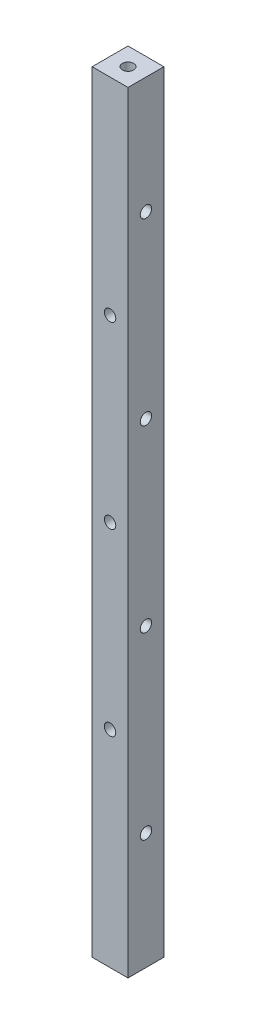
SolidWorks part; units mm, degrees
ref_plane "Front Plane" through (0, 0, 0) normal (0, 0, 1) x (1, 0, 0)
ref_plane "Top Plane" through (0, 0, 0) normal (0, 1, 0) x (1, 0, 0)
ref_plane "Right Plane" through (0, 0, 0) normal (1, 0, 0) x (0, 0, -1)
sketch "Sketch1" plane through (0, 0, 0) normal (0, 1, 0) x (1, 0, 0)
  line L1 (-6.35, -6.35) -> (6.35, -6.35)
  line L2 (-6.35, -6.35) -> (-6.35, 6.35)
  line L3 (-6.35, 6.35) -> (6.35, 6.35)
  line L4 (6.35, -6.35) -> (6.35, 6.35)
  line L5 (-6.35, -6.35) -> (6.35, 6.35) construction
  line L6 (-6.35, 6.35) -> (6.35, -6.35) construction
  point P0 (0, 0)
  dimension "D1" = 12.7
extrude "Boss-Extrude1" add sketch "Sketch1" along normal mid plane 273.05
sketch "Sketch2" [suppressed] plane through (0, 0, 6.35) normal (0, 0, 1) x (1, 0, 0)
  line L0 (0, -6.985) -> (0, 6.985) construction
  line L1 (-6.35, 247.65) -> (6.35, 247.65) construction
  point P0 (0, 241.3)
  point P7 (0, 144.78)
  point P8 (0, 48.26)
  point P9 (0, -48.26)
  point P10 (0, -144.78)
  point P11 (0, -241.3)
  dimension "D1" = 6.35
  dimension "D2" = 6
hole_wizard "#10 Clearance Hole1" [suppressed] positions "Sketch5" profile "Sketch7" hole size "#10" standard "ANSI Inch"
sketch "Sketch5" plane through (0, 0, 6.35) normal (0, 0, 1) x (1, 0, 0)
  point P0 (0, 241.3)
  point P3 (0, -241.3)
sketch "Sketch7" plane through (0, 241.3, 6.35) normal (1, 0, 0) x (0, -1, 0)
  line L0 (0, 0) -> (0, 12.7)
  line L1 (0, 12.7) -> (2.5527, 12.7)
  line L2 (2.5527, 12.7) -> (2.5527, 0)
  line L5 (2.5527, 0) -> (0, 0)
  line L11 (0, -6.35) -> (0, 107.95) construction
  dimension "Thru Hole Dia." = 5.1054
  dimension "Thru Hole Depth" = 12.7
hole_wizard "#10-32 Tapped Hole2" [suppressed] positions "Sketch8" profile "Sketch10" tap size "#10-32" standard "ANSI Inch"
sketch "Sketch8" plane through (0, 0, 6.35) normal (0, 0, 1) x (1, 0, 0)
  point P0 (0, 144.78)
  point P6 (0, -144.78)
  point P9 (0, -48.26)
  point P12 (0, 48.26)
sketch "Sketch10" plane through (0, 144.78, 6.35) normal (1, 0, 0) x (0, -1, 0)
  line L0 (0, 0) -> (0, 12.7)
  line L1 (0, 12.7) -> (2.0193, 12.7)
  line L2 (2.0193, 12.7) -> (2.0193, 0)
  line L5 (2.0193, 0) -> (0, 0)
  line L11 (0, -6.35) -> (0, 107.95) construction
  dimension "Thru Tap Drill Dia." = 4.0386
  dimension "Thru Tap Drill Depth" = 12.7
cosmetic thread "Hole Thread7" [suppressed] parameters "D2"=4.826
cosmetic thread "Hole Thread8" [suppressed] parameters "D2"=4.826
cosmetic thread "Hole Thread9" [suppressed] parameters "D2"=4.826
cosmetic thread "Hole Thread10" [suppressed] parameters "D2"=4.826
sketch "Sketch11" plane through (0, -136.525, 0) normal (0, -1, 0) x (1, 0, 0)
  point P0 (0, 0)
hole_wizard "#10-32 Tapped Hole3" positions "Sketch12" profile "Sketch14" tap size "#10-32" standard "ANSI Inch"
sketch "Sketch12" plane through (0, -136.525, 0) normal (0, -1, 0) x (-1, 0, 0)
  point P0 (0, 0)
sketch "Sketch14" plane through (0, -136.525, 0) normal (1, 0, 0) x (0, 0, -1)
  line L0 (0, 0) -> (0, 13.1513)
  line L1 (0, 13.1513) -> (2.0193, 11.938)
  line L2 (2.0193, 11.938) -> (2.0193, 0)
  line L5 (2.0193, 0) -> (0, 0)
  line L10 (0, 13.1513) -> (-2.0193, 11.938) construction
  line L11 (0, -6.35) -> (0, 107.95) construction
  dimension "Tap Drill Dia." = 4.0386
  dimension "Tap Drill Depth" = 11.938
  dimension "Drill Angle" = 118
cosmetic thread "Hole Thread11" parameters "D1"=9.652, "D2"=4.826
mirror "Mirror1" about plane through (0, 0, 0) normal (0, 1, 0) of "#10-32 Tapped Hole3"
cosmetic thread "Hole Thread12" parameters "D1"=9.652, "D2"=4.826
sketch "Sketch15" plane through (0, 0, -6.35) normal (0, 0, -1) x (-1, 0, 0)
  line L0 (0, 6.985) -> (0, -6.985) construction
  point P0 (0, 0)
  point P1 (0, 63.5)
  point P3 (0, -63.5)
  dimension "D1" = 63.5
  dimension "D2" = 63.5
hole_wizard "#10-32 Tapped Hole4" positions "Sketch16" profile "Sketch17" tap size "#10-32" standard "ANSI Inch" end condition up to next
sketch "Sketch16" plane through (0, 0, -6.35) normal (0, 0, -1) x (-1, 0, 0)
  point P0 (0, 63.5)
  point P3 (0, 0)
  point P6 (0, -63.5)
cosmetic thread "Hole Thread13" parameters "D2"=4.826
cosmetic thread "Hole Thread14" parameters "D2"=4.826
cosmetic thread "Hole Thread15" parameters "D2"=4.826
sketch "Sketch17" plane through (0, 63.5, -6.35) normal (1, 0, 0) x (0, 1, 0)
  line L0 (0, 0) -> (0, 12.7)
  line L1 (0, 12.7) -> (2.0193, 12.7)
  line L2 (2.0193, 12.7) -> (2.0193, 0)
  line L5 (2.0193, 0) -> (0, 0)
  line L11 (0, -6.35) -> (0, 107.95) construction
  dimension "Thru Tap Drill Dia." = 4.0386
  dimension "Thru Tap Drill Depth" = 12.7
sketch "Sketch18" plane through (-6.35, 0, 0) normal (-1, 0, 0) x (0, 0, 1)
  line L0 (0, -6.985) -> (0, 6.985) construction
  line L1 (6.985, 0) -> (-6.985, 0) construction
  point P1 (0, 31.75)
  point P2 (0, -31.75)
  point P5 (0, 95.25)
  point P6 (0, -95.25)
  dimension "D1" = 31.75
  dimension "D2" = 31.75
  dimension "D3" = 63.5
  dimension "D4" = 63.5
hole_wizard "#10-32 Tapped Hole5" positions "Sketch19" profile "Sketch20" tap size "#10-32" standard "ANSI Inch" end condition up to next
sketch "Sketch19" plane through (-6.35, 0, 0) normal (-1, 0, 0) x (0, 0, 1)
  point P0 (0, 95.25)
  point P3 (0, 31.75)
  point P6 (0, -31.75)
  point P9 (0, -95.25)
sketch "Sketch20" plane through (-6.35, 95.25, 0) normal (0, 1, 0) x (0, 0, 1)
  line L0 (0, 0) -> (0, 12.7)
  line L1 (0, 12.7) -> (2.0193, 12.7)
  line L2 (2.0193, 12.7) -> (2.0193, 0)
  line L5 (2.0193, 0) -> (0, 0)
  line L11 (0, -6.35) -> (0, 107.95) construction
  dimension "Thru Tap Drill Dia." = 4.0386
  dimension "Thru Tap Drill Depth" = 12.7
cosmetic thread "Hole Thread16" parameters "D2"=4.826
cosmetic thread "Hole Thread17" parameters "D2"=4.826
cosmetic thread "Hole Thread18" parameters "D2"=4.826
cosmetic thread "Hole Thread19" parameters "D2"=4.826
sketch "Sketch21" [suppressed] plane through (-6.35, 0, 0) normal (-1, 0, 0) x (0, 0, 1)
  line L0 (0, -6.985) -> (0, 6.985) construction
  point P0 (0, 0)
  point P1 (0, 96.52)
  point P3 (0, 193.04)
  point P6 (0, -96.52)
  point P7 (0, -193.04)
  dimension "D1" = 96.52
  dimension "D2" = 96.52
  dimension "D3" = 96.52
  dimension "D4" = 96.52
hole_wizard "#10-32 Tapped Hole6" [suppressed] positions "Sketch22" profile "Sketch23" tap size "#10-32" standard "ANSI Inch"
sketch "Sketch22" plane through (-6.35, 0, 0) normal (-1, 0, 0) x (0, 0, 1)
  point P0 (0, 193.04)
  point P3 (0, 96.52)
  point P6 (0, 0)
  point P9 (0, -96.52)
  point P12 (0, -193.04)
sketch "Sketch23" plane through (-6.35, 193.04, 0) normal (0, 1, 0) x (0, 0, 1)
  line L0 (0, 0) -> (0, 12.7)
  line L1 (0, 12.7) -> (2.0193, 12.7)
  line L2 (2.0193, 12.7) -> (2.0193, 0)
  line L5 (2.0193, 0) -> (0, 0)
  line L11 (0, -6.35) -> (0, 107.95) construction
  dimension "Thru Tap Drill Dia." = 4.0386
  dimension "Thru Tap Drill Depth" = 12.7
cosmetic thread "Hole Thread20" [suppressed] parameters "D2"=4.826
cosmetic thread "Hole Thread21" [suppressed] parameters "D2"=4.826
cosmetic thread "Hole Thread22" [suppressed] parameters "D2"=4.826
cosmetic thread "Hole Thread23" [suppressed] parameters "D2"=4.826
cosmetic thread "Hole Thread24" [suppressed] parameters "D2"=4.826
sketch "Sketch24" [suppressed] plane through (6.35, 0, 0) normal (1, 0, 0) x (0, 0, -1)
  point P0 (0, -25.4)
  point P1 (0, -71.12)
hole_wizard "#10-32 Tapped Hole7" [suppressed] positions "Sketch25" profile "Sketch27" tap size "#10-32" standard "ANSI Inch"
sketch "Sketch25" plane through (6.35, 0, 0) normal (1, 0, 0) x (0, 0, -1)
  point P0 (0, -25.4)
  point P4 (0, -71.12)
sketch "Sketch27" plane through (6.35, -25.4, 0) normal (0, 1, 0) x (0, 0, -1)
  line L0 (0, 0) -> (0, 12.7)
  line L1 (0, 12.7) -> (2.0193, 12.7)
  line L2 (2.0193, 12.7) -> (2.0193, 0)
  line L5 (2.0193, 0) -> (0, 0)
  line L11 (0, -6.35) -> (0, 107.95) construction
  dimension "Thru Tap Drill Dia." = 4.0386
  dimension "Thru Tap Drill Depth" = 12.7
cosmetic thread "Hole Thread25" [suppressed] parameters "D2"=4.826
cosmetic thread "Hole Thread26" [suppressed] parameters "D2"=4.826
